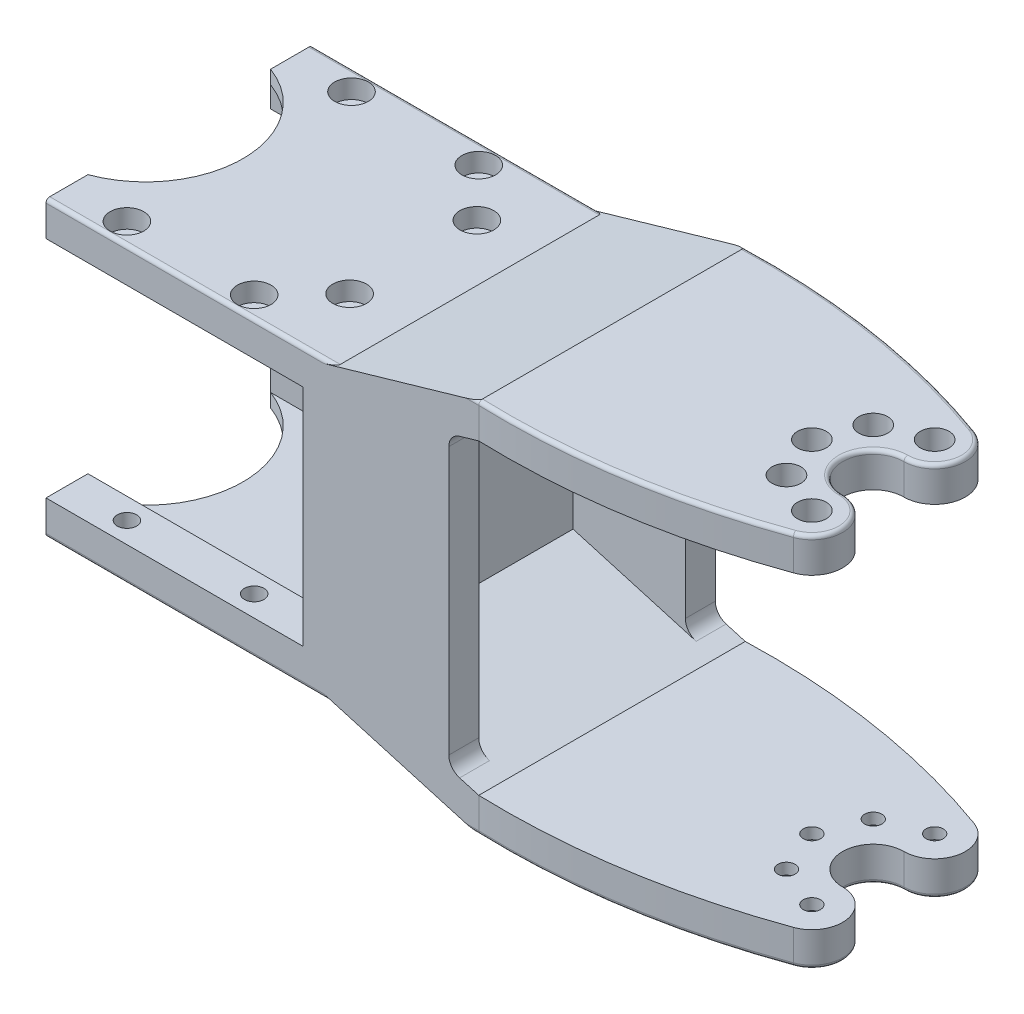
SolidWorks part; units mm, degrees
ref_plane "Front Plane" through (0, 0, 0) normal (0, 0, 1) x (1, 0, 0)
ref_plane "Top Plane" through (0, 0, 0) normal (0, 1, 0) x (1, 0, 0)
ref_plane "Right Plane" through (0, 0, 0) normal (1, 0, 0) x (0, 0, -1)
sketch "Sketch1" plane through (0, 0, 0) normal (0, 1, 0) x (1, 0, 0)
  line L0 (4.49, 12.2) -> (4.49, 17.8)
  line L1 (4.49, -12.2) -> (33.2, -12.2)
  line L3 (4.49, 12.2) -> (33.2, 12.2)
  line L4 (33.2, -12.2) -> (33.2, 12.2)
  line L5 (4.49, -17.8) -> (38.3, -17.8)
  line L6 (4.49, -17.8) -> (4.49, -12.2)
  line L7 (4.49, 17.8) -> (38.3, 17.8)
  line L8 (38.3, -17.8) -> (38.3, 17.8)
  line L9 (4.49, 17.8) -> (-12.2, 17.8) construction
  line L10 (4.49, 12.2) -> (-12.2, 12.2) construction
  line L11 (4.49, -12.2) -> (-12.2, -12.2) construction
  line L12 (4.49, -17.8) -> (-12.2, -17.8) construction
  line L13 (-12.2, 17.8) -> (-12.2, -17.8) construction
  line L14 (33.2, 0) -> (-11, 0) construction
  line L15 (38.3, 0) -> (33.2, 0) construction
  arc A0 (4.49, -12.2) -> (4.49, 12.2) centre (0, 0) ccw construction
  circle A1 centre (0, 0) radius 11 construction
  circle A2 centre (-4.5, 15) radius 1.3
  circle A3 centre (-4.5, 15) radius 2.25 construction
  circle A4 centre (12.5, 15) radius 1.3
  circle A5 centre (29.5, 15) radius 1.3
  circle A6 centre (-4.5, -15) radius 1.3
  circle A7 centre (12.5, -15) radius 1.3
  circle A8 centre (29.5, -15) radius 1.3
  circle A10 centre (35.75, -8.5) radius 1.3
  circle A11 centre (35.75, 8.5) radius 1.3
  point P16 (4.49, 15)
  point P36 (35.75, 0)
  dimension "D1" = 22
  dimension "D5" = 2.6
  dimension "D9" = 13
  dimension "D10" = 4.5
  dimension "D14" = 2.6
  dimension "D2" = 5.1
  dimension "D3" = 5.6
  dimension "D4" = 5.6
  dimension "D6" = 7.7
  dimension "D7" = 15
  dimension "D8" = 4.5
  dimension "D11" = 17
  dimension "D12" = 34
  dimension "D13" = 3.7
  dimension "D15" = 6.5
extrude "Boss-Extrude1" add sketch "Sketch1" along normal blind 2.8 contours L5 L8 L7 L0 L3 L4 L1 L6 A8 A4 A5 A7 A10 A11 | A2
sketch "Sketch2" plane through (0, 0, 0) normal (0, 1, 0) x (1, 0, 0)
  line L0 (4.49, 12.2) -> (33.2, 12.2) construction
  line L1 (4.49, -12.2) -> (33.2, -12.2) construction
  line L2 (33.2, -12.2) -> (33.2, 12.2) construction
  line L3 (4.49, 12.2) -> (33.2, 12.2)
  line L4 (4.49, -12.2) -> (33.2, -12.2)
  line L5 (33.2, -12.2) -> (33.2, 12.2)
  line L6 (4.49, -17.8) -> (4.49, -12.2) construction
  line L7 (4.49, -17.8) -> (38.3, -17.8) construction
  line L8 (38.3, -17.8) -> (38.3, 17.8) construction
  line L9 (4.49, 17.8) -> (38.3, 17.8) construction
  line L10 (4.49, 12.2) -> (4.49, 17.8) construction
  line L11 (4.49, -17.8) -> (4.49, -12.2)
  line L12 (4.49, -17.8) -> (38.3, -17.8)
  line L13 (38.3, -17.8) -> (38.3, 17.8)
  line L14 (4.49, 17.8) -> (38.3, 17.8)
  line L15 (4.49, 12.2) -> (4.49, 17.8)
  circle A0 centre (12.5, 15) radius 1.3 construction
  circle A1 centre (29.5, 15) radius 1.3 construction
  circle A2 centre (35.75, 8.5) radius 1.3 construction
  circle A3 centre (35.75, -8.5) radius 1.3 construction
  circle A4 centre (29.5, -15) radius 1.3 construction
  circle A5 centre (12.5, -15) radius 1.3 construction
  arc A6 (4.49, -12.2) -> (4.49, 12.2) centre (0, 0) ccw construction
  circle A7 centre (12.5, 15) radius 1.3
  circle A8 centre (29.5, 15) radius 1.3
  circle A9 centre (35.75, 8.5) radius 1.3
  circle A10 centre (35.75, -8.5) radius 1.3
  circle A11 centre (29.5, -15) radius 1.3
  circle A12 centre (12.5, -15) radius 1.3
  arc A13 (4.49, -12.2) -> (4.49, 12.2) centre (0, 0) ccw
extrude "Boss-Extrude2" add sketch "Sketch2" against normal blind 1.8 contours A13 L4 L5 L3 | L15 L3 L5 L4 L11 L12 L13 L14 A12 A11 A10 A9 A8 A7
sketch "Sketch3" plane through (0, -1.8, 0) normal (0, -1, 0) x (1, 0, 0)
  circle A0 centre (12.5, 15) radius 2.25
  circle A1 centre (29.5, 15) radius 2.25
  circle A2 centre (29.5, -15) radius 2.25
  circle A3 centre (12.5, -15) radius 2.25
  circle A4 centre (35.75, 8.5) radius 2.25
  circle A5 centre (35.75, -8.5) radius 2.25
  dimension "D1" = 4.5
  dimension "D4" = 17
  dimension "D5" = 4.5
  dimension "D2" = 2
  dimension "D3" = 2
extrude "Cut-Extrude1" cut sketch "Sketch3" against normal blind 2.5
sketch "Sketch4" plane through (38.3, 0, 0) normal (1, 0, 0) x (0, 0, -1)
  line L4 (-17.8, 2.8) -> (-17.8, -1.8)
  line L5 (-17.8, -1.8) -> (17.8, -1.8)
  line L6 (17.8, -1.8) -> (17.8, 2.8)
  line L7 (17.8, 2.8) -> (-17.8, 2.8)
  line L8 (-17.8, 2.8) -> (-17.8, -1.8)
  line L9 (-17.8, -1.8) -> (17.8, -1.8)
  line L10 (17.8, -1.8) -> (17.8, 2.8)
  line L11 (17.8, 2.8) -> (-17.8, 2.8)
  dimension "D1" = 0
extrude "Boss-Extrude3" add sketch "Sketch4" along normal blind 5
sketch "Sketch5" plane through (0, 2.8, 0) normal (0, 1, 0) x (1, 0, 0)
  line L0 (4.49, 17.8) -> (43.3, 17.8) construction
  line L1 (38.8, 17.8) -> (43.3, 17.8)
  line L2 (38.8, 17.8) -> (38.8, -17.8)
  line L3 (38.8, -17.8) -> (43.3, -17.8)
  line L4 (43.3, 17.8) -> (43.3, -17.8)
  dimension "D1" = 4.5
extrude "Boss-Extrude4" add sketch "Sketch5" along normal blind 15
mirror "Mirror3" about plane through (0, 17.8, 0) normal (0, 1, 0) of "Boss-Extrude4", "Boss-Extrude3", "Cut-Extrude1", "Boss-Extrude2", "Boss-Extrude1"
ref_plane "Plane1" through (0, 38.3, 0) normal (0, -1, 0) x (-1, 0, 0)
sketch "Sketch6" plane through (0, 38.3, 0) normal (0, -1, 0) x (-1, 0, 0)
  line L0 (-13, 0) -> (-97.2, 0) construction
  line L1 (-62.3, 17.8) -> (-62.3, -17.8)
  arc A2 (-97.2, -4.1) -> (-98.5927, -12.0562) centre (-97.2, -8.2) ccw
  arc A3 (-98.5927, 12.0562) -> (-97.2, 4.1) centre (-97.2, 8.2) ccw
  circle A5 centre (-97.2, 8.2) radius 1.15
  circle A11 centre (-97.2, 8.2) radius 1.15
  arc A12 (-98.5927, 12.0562) -> (-62.3, 17.8) centre (-65.4832, -79.618) cw
  arc A13 (-98.5927, -12.0562) -> (-62.3, -17.8) centre (-65.4832, 79.618) ccw
  circle A17 centre (-91.4017, 5.7983) radius 1.15
  arc A18 (-97.2, -4.1) -> (-97.2, 4.1) centre (-97.2, 0) ccw
  circle A19 centre (-89, 0) radius 1.15
  arc A20 (-4.49, 12.2) -> (-4.49, -12.2) centre (0, 0) ccw construction
  circle A21 centre (-91.4017, -5.7983) radius 1.15
  circle A23 centre (-97.2, -8.2) radius 1.15
  point P9 (-13, 0)
  point P10 (0, 0)
  point P11 (0, 0)
  point P22 (-97.2, 0)
  point P31 (-97.2, 0)
  point P42 (-97.2, 0)
  dimension "D2" = 8.2
  dimension "D3" = 2.3
  dimension "D4" = 5
  dimension "D5" = 97.47
  dimension "D6" = 8.2
  dimension "D1" = 19
  dimension "D7" = 39
extrude "Boss-Extrude5" add sketch "Sketch6" against normal blind 4.6
sketch "Sketch7" plane through (43.3, 0, 0) normal (1, 0, 0) x (0, 0, -1)
  line L0 (17.8, -1.8) -> (17.8, 37.4) construction
  line L1 (-17.8, 37.4) -> (17.8, 37.4)
  line L2 (-17.8, 37.4) -> (-17.8, 32.8)
  line L3 (-17.8, 32.8) -> (17.8, 32.8)
  line L4 (17.8, 37.4) -> (17.8, 32.8)
  dimension "D1" = 4.6
ref_plane "Plane2" through (0, 17.8, 0) normal (0, 1, 0) x (1, 0, 0)
sketch "Sketch11" plane through (62.3, 0, 0) normal (-1, 0, 0) x (0, 0, 1)
  line L4 (-17.8, 38.3) -> (17.8, 38.3)
  line L5 (17.8, 38.3) -> (17.8, 42.9)
  line L6 (17.8, 42.9) -> (-17.8, 42.9)
  line L7 (-17.8, 42.9) -> (-17.8, 38.3)
  line L8 (-17.8, 38.3) -> (17.8, 38.3)
  line L9 (17.8, 38.3) -> (17.8, 42.9)
  line L10 (17.8, 42.9) -> (-17.8, 42.9)
  line L11 (-17.8, 42.9) -> (-17.8, 38.3)
  dimension "D1" = 0
loft "Loft1" add profiles "Sketch7", "Sketch11"
mirror "Mirror4" about plane through (0, 17.8, 0) normal (0, 1, 0) of "Loft1", "Boss-Extrude5"
mirror "Mirror5" about plane through (0, 17.8, 0) normal (0, 1, 0) of "Boss-Extrude5"
sketch "Sketch12" plane through (0, 0, 17.8) normal (0, 0, 1) x (1, 0, 0)
  line L0 (58.3, 37.1421) -> (58.3, -1.5421)
  line L1 (43.3, 32.8) -> (62.3, 38.3) construction
  line L2 (43.3, 2.8) -> (62.3, -2.7) construction
  line L3 (58.3, 37.1421) -> (43.3, 32.8)
  line L4 (43.3, 32.8) -> (43.3, 2.8)
  line L5 (43.3, 2.8) -> (58.3, -1.5421)
  dimension "D1" = 15
extrude "Boss-Extrude6" add sketch "Sketch12" against normal blind 4
mirror "Mirror6" about plane through (0, 0, 0) normal (0, 0, 1) of "Boss-Extrude6"
fillet "Fillet2" radius 2 4 edges at (58.3, -1.5421, 15.8) (58.3, -1.5421, -15.8) (58.3, 37.1421, -15.8) (58.3, 37.1421, 15.8)
sketch "Sketch13" plane through (0, 42.9, 0) normal (0, 1, 0) x (1, 0, 0)
  circle A0 centre (97.2, 8.2) radius 1.925
  circle A1 centre (91.4017, 5.7983) radius 1.925
  circle A2 centre (89, 0) radius 1.925
  circle A3 centre (91.4017, -5.7983) radius 1.925
  circle A4 centre (97.2, -8.2) radius 1.925
  point P3 (97.2, 0)
  point P6 (0, 0)
  point P7 (97.2, 0)
  point P15 (97.2, 0)
  point P16 (91.4017, 5.7983)
  dimension "D1" = 3.85
  dimension "D2" = 5
extrude "Cut-Extrude2" cut sketch "Sketch13" against normal blind 3.1
ref_plane "Plane3" through (0, 17.8, 0) normal (0, 1, 0) x (1, 0, 0)
mirror "Mirror7" about plane through (0, 17.8, 0) normal (0, 1, 0) of "Cut-Extrude2"
fillet "Fillet10" radius 0.5 15 edges at (101.2386, -7.3, -7.493) (93.1, -7.3, 0) (101.2386, -7.3, 7.493) (101.2386, 42.9, -7.493) (93.1, 42.9, 0) (101.2386, 42.9, 7.493) (18.845, 0, 12.2) (23.895, 37.4, -17.8) (23.895, 37.4, 17.8)
